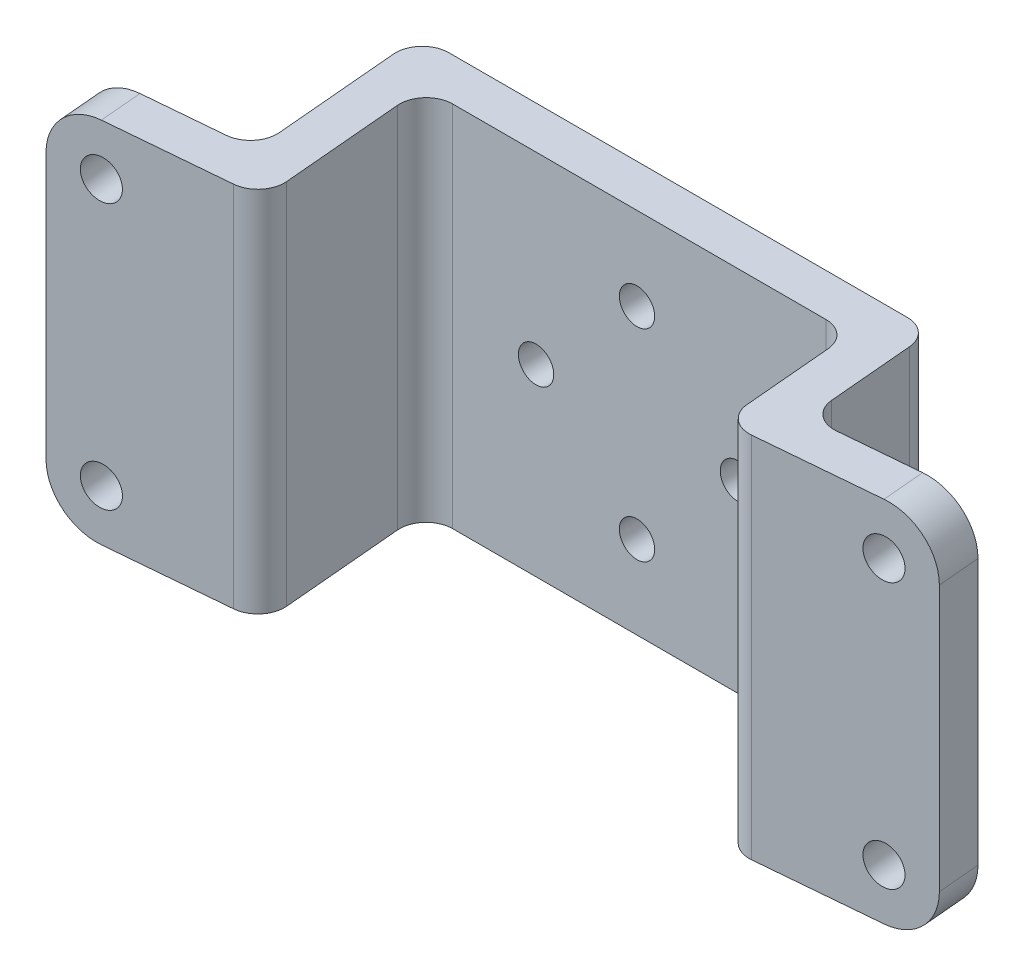
SolidWorks part; units mm, degrees
ref_plane "Front Plane" through (0, 0, 0) normal (0, 0, 1) x (1, 0, 0)
ref_plane "Top Plane" through (0, 0, 0) normal (0, 1, 0) x (1, 0, 0)
ref_plane "Right Plane" through (0, 0, 0) normal (1, 0, 0) x (0, 0, -1)
sketch "Sketch1" plane through (0, 0, 0) normal (0, 0, 1) x (1, 0, 0)
  line L0 (0, 9.5) -> (-9.5, 0) construction
  line L1 (-17.3125, -17.3125) -> (17.3125, -17.3125)
  line L2 (-17.3125, -17.3125) -> (-17.3125, 17.3125)
  line L3 (-17.3125, 17.3125) -> (17.3125, 17.3125)
  line L4 (17.3125, -17.3125) -> (17.3125, 17.3125)
  line L5 (-17.3125, -17.3125) -> (17.3125, 17.3125) construction
  line L6 (-17.3125, 17.3125) -> (17.3125, -17.3125) construction
  line L7 (-9.5, 0) -> (0, -9.5) construction
  line L8 (0, -9.5) -> (9.5, 0) construction
  line L9 (9.5, 0) -> (0, 9.5) construction
  line L10 (0, 9.5) -> (0, -9.5)
  circle A0 centre (0, 9.5) radius 1.6625
  circle A1 centre (9.5, 0) radius 1.6625
  circle A2 centre (-9.5, 0) radius 1.6625
  circle A3 centre (0, -9.5) radius 1.6625
  point P0 (0, 0)
  dimension "D3" = 3.325
  dimension "D2" = 19
  dimension "D1" = 34.625
sketch "Sketch4" plane through (0, 0, 0) normal (0, 1, 0) x (0, 0, -1)
  line L0 (0, 0) -> (-2.8754, 32.8656) construction
  line L1 (0, 19.0438) -> (0, -19.0438) construction
  dimension "D1" = 5
ref_plane "Plane1" through (0, 0, 0) normal (-0.0872, 0, -0.9962) x (-0.9962, 0, 0.0872)
sketch "Sketch12" plane through (0, 0, 0) normal (1, 0, 0) x (0, 0, -1)
  line L0 (0, 0) -> (-15, 0) construction
  dimension "D1" = 15
ref_plane "Plane2" through (1.3024, 0, 14.8861) normal (-0.0872, 0, -0.9962) x (-0.9962, 0, 0.0872)
extrude "Boss-Extrude1" add sketch "Sketch1" against normal blind 4
sketch "Sketch6" plane through (378.2774, 0, -18.095) normal (-0.0872, 0, -0.9962) x (0, 1, 0)
  line L1 (-19.05, -359.365) -> (19.05, -359.365) construction
  line L2 (-19.05, -359.365) -> (-19.05, -397.465) construction
  line L3 (-19.05, -397.465) -> (19.05, -397.465) construction
  line L4 (19.05, -359.365) -> (19.05, -397.465) construction
  line L5 (-19.05, -359.365) -> (19.05, -397.465) construction
  line L6 (-19.05, -397.465) -> (19.05, -359.365) construction
  line L7 (-12.5, -344.415) -> (12.5, -344.415) construction
  line L8 (-12.5, -344.415) -> (-12.5, -412.415) construction
  line L9 (-12.5, -412.415) -> (12.5, -412.415) construction
  line L10 (12.5, -344.415) -> (12.5, -412.415) construction
  line L11 (-12.5, -344.415) -> (12.5, -412.415) construction
  line L12 (-12.5, -412.415) -> (12.5, -344.415) construction
  line L14 (0, -339.6025) -> (0, -378.415) construction
  line L15 (0, -378.415) -> (-17.3125, -378.415) construction
  line L18 (-12.5, -339.6025) -> (12.5, -339.6025)
  line L19 (-17.3125, -344.415) -> (-17.3125, -358.415)
  line L20 (-17.3125, -358.415) -> (-17.3125, -378.415)
  line L21 (-17.3125, -358.415) -> (17.3125, -358.415)
  line L22 (17.3125, -344.415) -> (17.3125, -358.415)
  line L23 (-17.3125, -412.415) -> (-17.3125, -398.415)
  line L24 (-12.5, -417.2275) -> (12.5, -417.2275)
  line L25 (17.3125, -412.415) -> (17.3125, -398.415)
  line L26 (-17.3125, -398.415) -> (17.3125, -398.415)
  arc A0 (-12.5, -339.6025) -> (-17.3125, -344.415) centre (-12.5, -344.415) ccw
  arc A1 (12.5, -339.6025) -> (17.3125, -344.415) centre (12.5, -344.415) cw
  arc A2 (-12.5, -417.2275) -> (-17.3125, -412.415) centre (-12.5, -412.415) cw
  arc A3 (12.5, -417.2275) -> (17.3125, -412.415) centre (12.5, -412.415) ccw
  point P0 (0, -378.415)
  point P6 (0, -378.415)
  point P18 (0, -358.415)
  dimension "D6" = 4.8125
  dimension "D1" = 38.1
  dimension "D2" = 38.1
  dimension "D3" = 25
  dimension "D4" = 68
  dimension "D5" = 20
extrude "Boss-Extrude2" add sketch "Sketch6" along normal blind 4 separate body contours L24 A3 L25 L26 L23 A2 | A1 L18 A0 L19 L21 L22
sketch "Sketch7" plane through (1.3024, 0, 14.8861) normal (-0.0872, 0, -0.9962) x (-0.9962, 0, 0.0872)
  line L0 (34, 17.3125) -> (20, 17.3125) construction
  line L1 (20, -17.3125) -> (24, -17.3125)
  line L2 (20, -17.3125) -> (20, 17.3125)
  line L3 (20, 17.3125) -> (24, 17.3125)
  line L4 (24, -17.3125) -> (24, 17.3125)
  line L5 (-34, 17.3125) -> (-20, 17.3125) construction
  line L6 (-20, -17.3125) -> (-24, -17.3125)
  line L7 (-20, -17.3125) -> (-20, 17.3125)
  line L8 (-20, 17.3125) -> (-24, 17.3125)
  line L9 (-24, -17.3125) -> (-24, 17.3125)
  dimension "D1" = 4
extrude "Boss-Extrude3" add sketch "Sketch7" along normal up to surface (20.708 mm away)
sketch "Sketch8" plane through (-17.3125, 0, 0) normal (1, 0, 0) x (0, -1, 0)
  line L12 (-17.3125, 0) -> (17.3125, 0)
  line L13 (-17.3125, 4) -> (-17.3125, 0)
  line L14 (17.3125, 4) -> (-17.3125, 4)
  line L15 (17.3125, 0) -> (17.3125, 4)
  line L16 (-17.3125, 0) -> (17.3125, 0)
  line L17 (-17.3125, 4) -> (-17.3125, 0)
  line L18 (17.3125, 4) -> (-17.3125, 4)
  line L19 (17.3125, 0) -> (17.3125, 4)
  dimension "D1" = 0
extrude "Boss-Extrude4" add sketch "Sketch8" along normal up to surface (2.7639 mm away)
sketch "Sketch9" plane through (17.3125, 0, 0) normal (-1, 0, 0) x (0, -1, 0)
  line L16 (17.3125, 0) -> (-17.3125, 0)
  line L17 (17.3125, -4) -> (17.3125, 0)
  line L18 (-17.3125, -4) -> (17.3125, -4)
  line L19 (-17.3125, 0) -> (-17.3125, -4)
  line L29 (17.3125, 0) -> (-17.3125, 0)
  line L30 (17.3125, -4) -> (17.3125, 0)
  line L31 (-17.3125, -4) -> (17.3125, -4)
  line L32 (-17.3125, 0) -> (-17.3125, -4)
  dimension "D1" = 0
extrude "Boss-Extrude5" add sketch "Sketch9" along normal up to surface (2.7639 mm away)
hole_wizard "#6 Clearance Hole1" positions "Sketch10" profile "Sketch11" hole size "#6" standard "ANSI Inch" end condition through all
sketch "Sketch10" plane through (1.3024, 0, 14.8861) normal (0.0872, 0, 0.9962) x (0.9924, 0.0872, -0.0868)
  arc A0 (-32.3617, 20.2099) -> (-37.5754, 15.8352) centre (-32.7812, 15.4157) ccw construction
  point P0 (-34.9601, -9.4891)
  point P3 (-32.7812, 15.4157)
  point P5 (34.9601, 9.4891)
  point P8 (32.7812, -15.4157)
sketch "Sketch11" plane through (-32.5683, -12.5, 17.8494) normal (0, 1, 0) x (0.9962, 0, -0.0872)
  line L0 (0, 0) -> (0, 22.2144)
  line L1 (0, 22.2144) -> (1.8288, 22.2144)
  line L2 (1.8288, 22.2144) -> (1.8288, 0)
  line L5 (1.8288, 0) -> (0, 0)
  line L11 (0, -6.35) -> (0, 107.95) construction
  dimension "Thru Hole Dia." = 3.6576
  dimension "Thru Hole Depth" = 22.2144
fillet "Fillet1" radius 2.5 8 edges at (-20.0764, 0, 0) (20.0764, 0, 0) (24.8624, 0, 8.8095) (23.7417, 0, -4) (-22.9549, 0, 12.993) (-24.4416, 0, -4) (21.2263, 0, 13.1429) (-18.6215, 0, 16.6292)
equation "\"od square tube\"= 1.375in"
equation "\"camera mount hole diameter\"= 0.1440in"
equation "\"cam mount hole separation\"= 45mm"
equation "\"frame mount hole diameter\"= 3.125mm"
equation "\"tolerance\"= .2mm"
equation "\"D3@Sketch1\"= \"frame mount hole diameter\" + \"tolerance\""
equation "\"horizontal angle\" = 120"
equation "\"vertical angle\" = 5"
equation "\"frame mount hole separation\"= 19mm"
equation "\"washer counterbore\"= 4.7625mm + 0.05mm"
equation "\"D6@Sketch6\"=\"washer counterbore\""
equation "\"D1@Sketch1\"=\"washer counterbore\"*2 + 25"
equation "\"offset\" = 15mm"
equation "\"D1@Sketch12\"=\"offset\""
equation "\"D1@Sketch4\"=\"vertical angle\""
